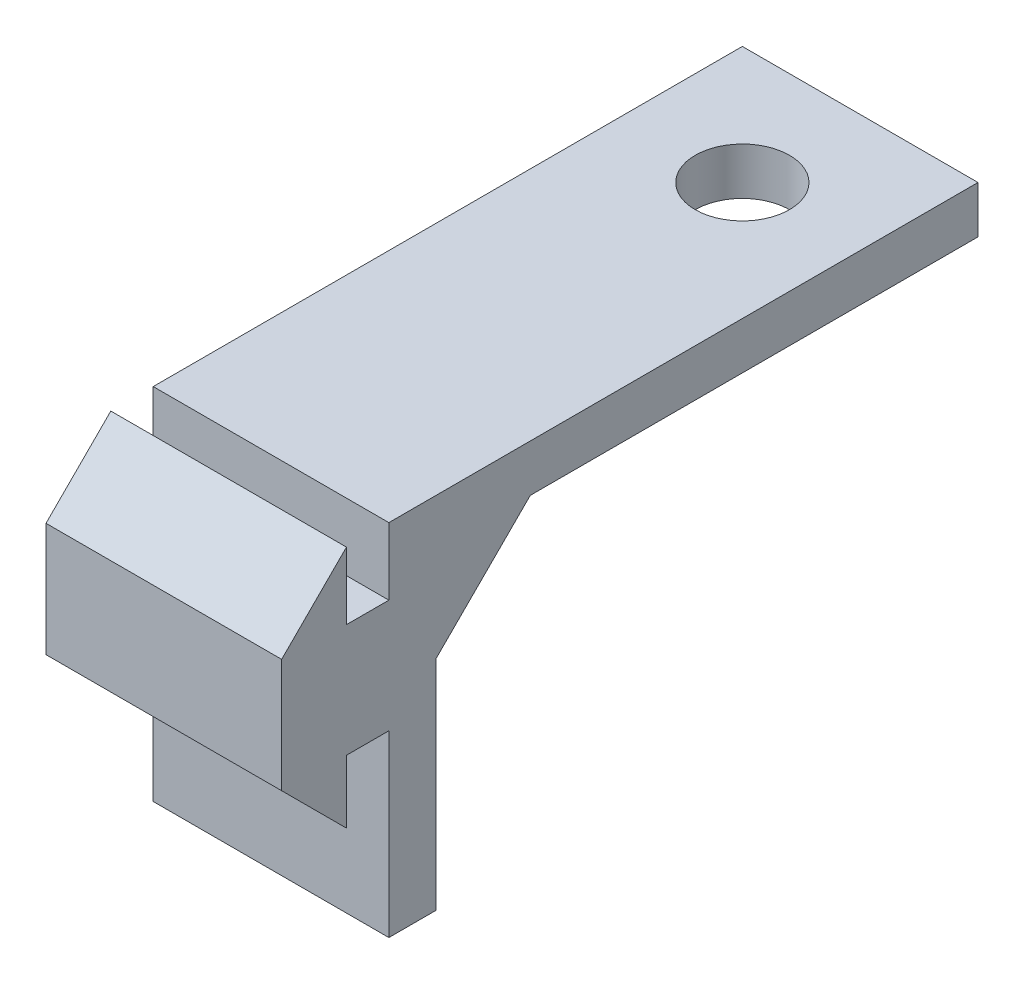
SolidWorks part; units mm, degrees
ref_plane "Front Plane" through (0, 0, 0) normal (0, 0, 1) x (1, 0, 0)
ref_plane "Top Plane" through (0, 0, 0) normal (0, 1, 0) x (1, 0, 0)
ref_plane "Right Plane" through (0, 0, 0) normal (1, 0, 0) x (0, 0, -1)
sketch "Sketch1" plane through (0, 0, 0) normal (1, 0, 0) x (0, 0, -1)
  line L0 (0, 0) -> (0, 7.6)
  line L1 (0, 12.4) -> (0, 15.25)
  line L2 (25, 15.25) -> (0, 15.25)
  line L3 (2, 0) -> (2, 9.25)
  line L4 (6, 13.25) -> (25, 13.25)
  line L5 (2, 0) -> (0, 0)
  line L6 (0, 9.25) -> (2, 9.25) construction
  line L7 (0, 9.25) -> (-1.8, 9.25) construction
  line L8 (20, 15.25) -> (20, 13.25) construction
  line L11 (25, 15.25) -> (25, 13.25)
  line L13 (-1.8, 9.25) -> (-1.8, 12.4) construction
  line L14 (-1.8, 12.4) -> (-1.8, 15.25)
  line L15 (-1.8, 15.25) -> (-4.55, 12.5)
  line L16 (-1.8, 9.25) -> (-1.8, 7.6) construction
  line L17 (-1.8, 7.6) -> (-1.8, 4.9217)
  line L18 (-1.8, 4.9217) -> (-4.55, 7.6717)
  line L19 (-4.55, 12.5) -> (-4.55, 7.6717)
  line L20 (-1.8, 12.4) -> (0, 12.4)
  line L21 (-1.8, 7.6) -> (0, 7.6)
  line L22 (2, 9.25) -> (6, 13.25)
  dimension "D1" = 45
  dimension "D2" = 4
  dimension "D3" = 2
  dimension "D4" = 2
  dimension "D5" = 20
  dimension "D6" = 5
extrude "Boss-Extrude2" add sketch "Sketch1" along normal blind 10
sketch "Sketch2" plane through (0, 15.25, 0) normal (0, 1, 0) x (1, 0, 0)
  line L0 (10, 20) -> (0, 20)
  circle A0 centre (5, 20) radius 2
extrude "Cut-Extrude9" cut sketch "Sketch2" against normal blind 3
